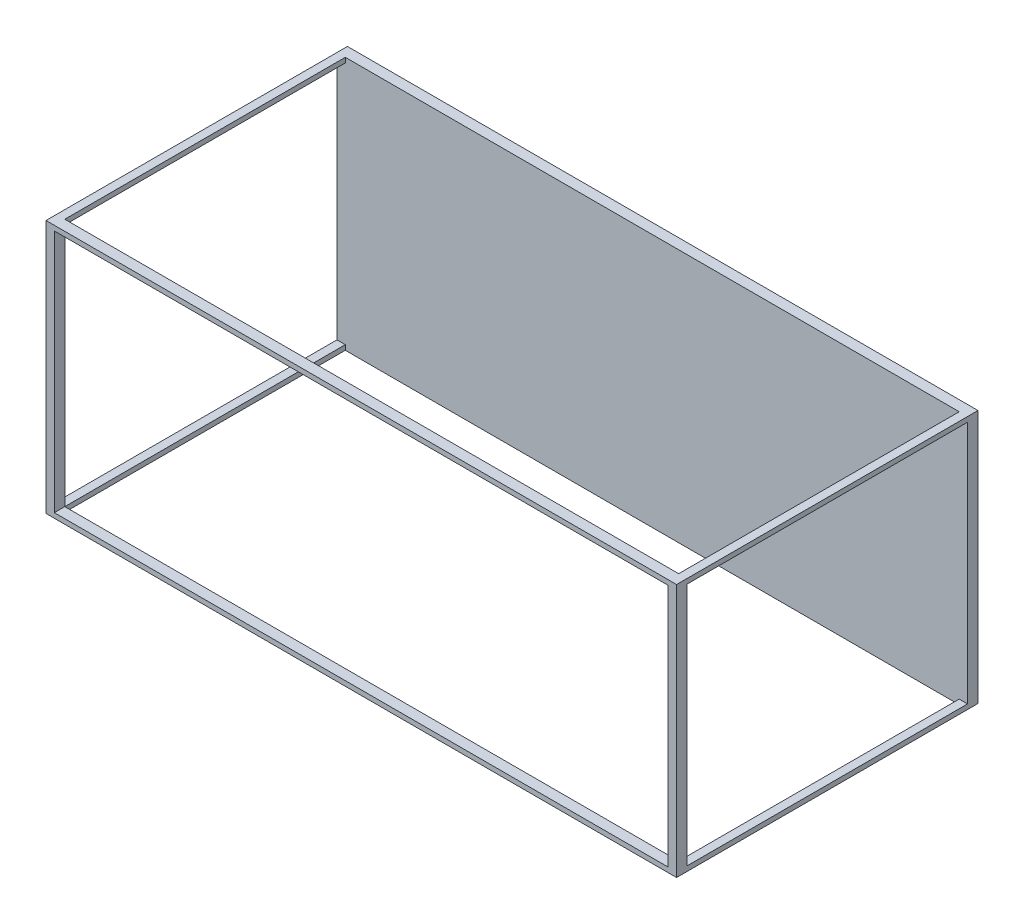
SolidWorks part; units mm, degrees
ref_plane "Front Plane" through (0, 0, 0) normal (0, 0, 1) x (1, 0, 0)
ref_plane "Top Plane" through (0, 0, 0) normal (0, 1, 0) x (1, 0, 0)
ref_plane "Right Plane" through (0, 0, 0) normal (1, 0, 0) x (0, 0, -1)
sketch "Sketch1" plane through (0, 0, 0) normal (0, 0, 1) x (1, 0, 0)
  line L1 (-2964.258, 1392.1237) -> (2933.742, 1392.1237)
  line L2 (-2964.258, 1392.1237) -> (-2964.258, -951.8763)
  line L3 (-2964.258, -951.8763) -> (2933.742, -951.8763)
  line L4 (2933.742, 1392.1237) -> (2933.742, -951.8763)
  line L5 (-3044.258, 1439.1237) -> (3013.742, 1439.1237)
  line L6 (-3044.258, 1439.1237) -> (-3044.258, -998.8763)
  line L7 (-3044.258, -998.8763) -> (3013.742, -998.8763)
  line L8 (3013.742, 1439.1237) -> (3013.742, -998.8763)
  dimension "D1" = 6058
  dimension "D2" = 2344
  dimension "D3" = 80
  dimension "D4" = 47
  dimension "D5" = 2438
  dimension "D6" = 5898
extrude "Boss-Extrude1" add sketch "Sketch1" along normal blind 2896 contours L6 L5 L8 L7
sketch "Sketch4" plane through (0, -998.8763, 0) normal (0, -1, 0) x (1, 0, 0)
  line L0 (-3044.258, 0) -> (3013.742, 0) construction
  line L3 (-2964.258, 100.5) -> (2933.742, 100.5)
  line L8 (-2964.258, 100.5) -> (2933.742, 100.5)
  line L9 (-2964.258, 100.5) -> (-2964.258, 2795.5)
  line L10 (-2964.258, 2795.5) -> (2933.742, 2795.5)
  line L11 (2933.742, 100.5) -> (2933.742, 2795.5)
  dimension "D1" = 100.5
  dimension "D2" = 5898
  dimension "D3" = 2695
sketch "Sketch6" plane through (0, 0, 0) normal (0, 0, -1) x (-1, 0, 0)
  line L0 (-3013.742, 1439.1237) -> (-3013.742, -998.8763) construction
  line L1 (3044.258, 1439.1237) -> (-3013.742, 1439.1237)
  line L2 (3044.258, 1439.1237) -> (3044.258, 1392.1237)
  line L3 (3044.258, 1392.1237) -> (-3013.742, 1392.1237)
  line L4 (-3013.742, 1439.1237) -> (-3013.742, 1392.1237)
  line L6 (3044.258, -998.8763) -> (-3013.742, -998.8763)
  line L7 (3044.258, -998.8763) -> (3044.258, -951.8763)
  line L8 (3044.258, -951.8763) -> (-3013.742, -951.8763)
  line L9 (-3013.742, -998.8763) -> (-3013.742, -951.8763)
  dimension "D1" = 47
  dimension "D2" = 47
extrude "Cut-Extrude1" cut sketch "Sketch4" against normal through all contours L3 L11 L10 L9
sketch "Sketch8" plane through (0, 0, 2896) normal (0, 0, 1) x (1, 0, 0)
  line L0 (-3044.258, 1439.1237) -> (-3044.258, -998.8763) construction
  line L1 (-2964.258, 1392.1237) -> (2933.742, 1392.1237)
  line L2 (-2964.258, 1392.1237) -> (-2964.258, -951.8763)
  line L3 (-2964.258, -951.8763) -> (2933.742, -951.8763)
  line L4 (2933.742, 1392.1237) -> (2933.742, -951.8763)
  line L5 (-3044.258, 1439.1237) -> (3013.742, 1439.1237) construction
  dimension "D1" = 5898
  dimension "D2" = 80
  dimension "D3" = 2344
  dimension "D4" = 47
extrude "Cut-Extrude2" cut sketch "Sketch8" against normal blind 180 and the other way through all contours L2 L1 L4 L3
sketch "Sketch9" plane through (-3044.258, 0, 0) normal (-1, 0, 0) x (0, 0, 1)
  line L0 (2896, -998.8763) -> (0, -998.8763) construction
  line L1 (2795.5, 1392.1237) -> (100.5, 1392.1237)
  line L2 (2795.5, 1392.1237) -> (2795.5, -951.8763)
  line L3 (2795.5, -951.8763) -> (100.5, -951.8763)
  line L4 (100.5, 1392.1237) -> (100.5, -951.8763)
  line L5 (2896, 1439.1237) -> (2896, -998.8763) construction
  dimension "D1" = 2344
  dimension "D2" = 47
  dimension "D3" = 2695
  dimension "D4" = 100.5
extrude "Cut-Extrude3" cut sketch "Sketch9" against normal through all both and the other way through all
